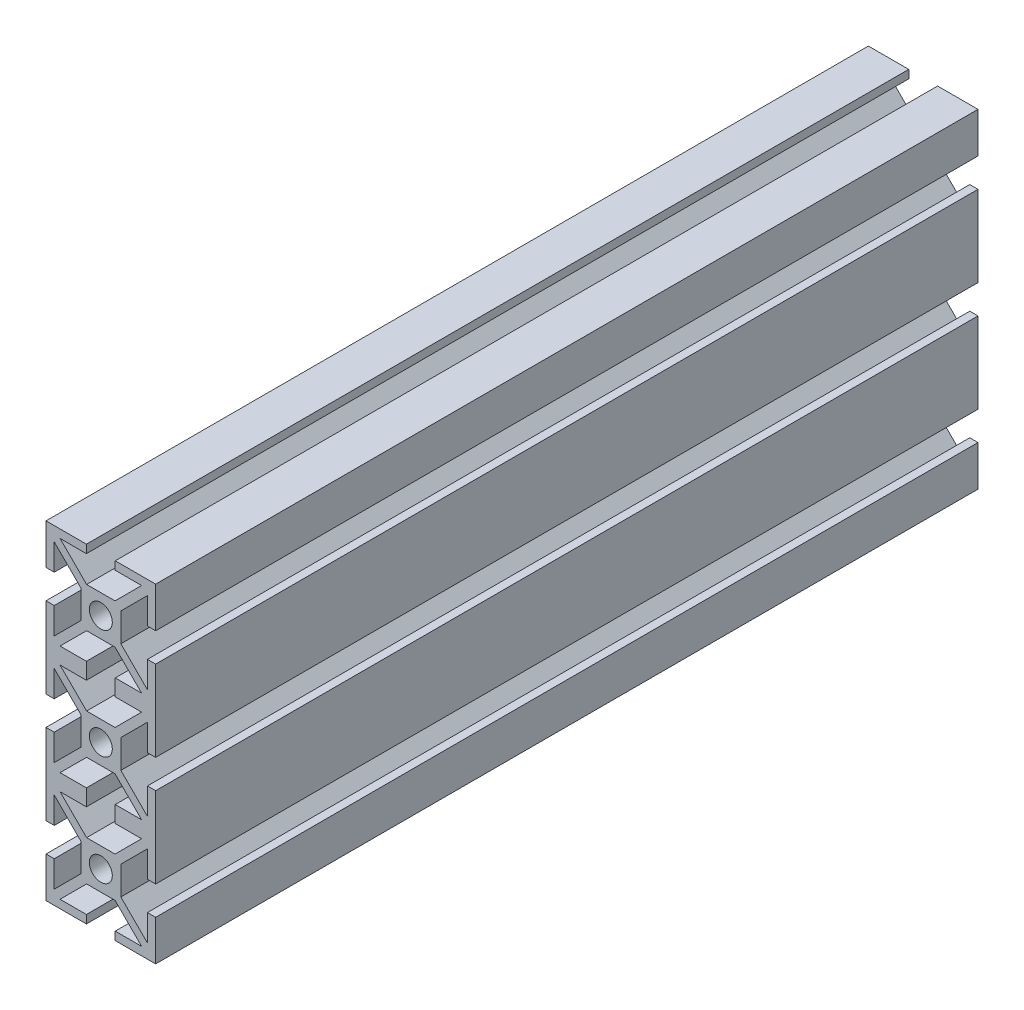
SolidWorks part; units mm, degrees
material "6061-T4 (SS)"
ref_plane "Front Plane" through (0, 0, 0) normal (0, 0, 1) x (1, 0, 0)
ref_plane "Top Plane" through (0, 0, 0) normal (0, 1, 0) x (1, 0, 0)
ref_plane "Right Plane" through (0, 0, 0) normal (1, 0, 0) x (0, 0, -1)
sketch "Sketch1" plane through (0, 0, 0) normal (0, 0, 1) x (1, 0, 0)
  line L0 (0, 20) -> (20, 0) construction
  line L1 (0, 0) -> (20, 0) construction
  line L2 (0, 0) -> (0, 20) construction
  line L3 (0, 20) -> (20, 20) construction
  line L4 (20, 0) -> (20, 20) construction
  line L5 (20, 20) -> (0, 0) construction
  line L6 (18.5, 1.5) -> (18.5, 0) construction
  line L7 (1.5, 1.5) -> (18.5, 1.5) construction
  line L8 (1.5, 1.5) -> (1.5, 18.5) construction
  line L9 (1.5, 18.5) -> (18.5, 18.5) construction
  line L10 (18.5, 1.5) -> (18.5, 18.5) construction
  line L11 (18.5, 1.5) -> (20, 1.5) construction
  line L12 (6.345, 12.5943) -> (1.5, 17.4393)
  line L13 (13.655, 6.345) -> (6.345, 6.345) construction
  line L14 (13.655, 6.345) -> (13.655, 13.655) construction
  line L15 (13.655, 13.655) -> (6.345, 13.655) construction
  line L16 (6.345, 6.345) -> (6.345, 13.655) construction
  line L17 (7.4057, 13.655) -> (2.5607, 18.5)
  line L18 (2.5607, 18.5) -> (2.0303, 17.9697) construction
  line L19 (2.0303, 17.9697) -> (1.5, 17.4393) construction
  line L20 (6.345, 7.4057) -> (6.345, 12.5943)
  line L21 (12.5943, 13.655) -> (17.4393, 18.5)
  line L22 (17.4393, 18.5) -> (17.9697, 17.9697) construction
  line L23 (17.9697, 17.9697) -> (18.5, 17.4393) construction
  line L24 (18.5, 17.4393) -> (13.655, 12.5943)
  line L25 (13.655, 7.4057) -> (18.5, 2.5607)
  line L26 (18.5, 2.5607) -> (17.9697, 2.0303) construction
  line L27 (17.4393, 1.5) -> (12.5943, 6.345)
  line L28 (7.4057, 6.345) -> (2.5607, 1.5)
  line L29 (17.9697, 2.0303) -> (17.4393, 1.5) construction
  line L30 (1.5, 2.5607) -> (6.345, 7.4057)
  line L31 (2.5607, 1.5) -> (2.0303, 2.0303) construction
  line L32 (2.0303, 2.0303) -> (1.5, 2.5607) construction
  line L33 (7.4057, 13.655) -> (12.5943, 13.655)
  line L34 (13.655, 12.5943) -> (13.655, 7.4057)
  line L36 (12.5943, 6.345) -> (7.4057, 6.345)
  line L37 (0, 10) -> (1.5, 10) construction
  line L38 (0.75, 12.63) -> (0.75, 10) construction
  line L39 (0.75, 10) -> (0.75, 7.37) construction
  line L40 (1.5, 12.63) -> (0, 12.63)
  line L41 (1.5, 7.37) -> (0, 7.37)
  line L42 (10, 1.5) -> (10, 0) construction
  line L43 (10, 0.75) -> (12.63, 0.75) construction
  line L44 (10, 0.75) -> (7.37, 0.75) construction
  line L45 (12.63, 0) -> (12.63, 1.5)
  line L46 (7.37, 1.5) -> (7.37, 0)
  line L47 (18.5, 12.63) -> (20, 12.63)
  line L48 (18.5, 7.37) -> (20, 7.37)
  line L49 (7.37, 20) -> (7.37, 18.5)
  line L50 (12.63, 20) -> (12.63, 18.5)
  line L51 (2.5607, 1.5) -> (7.37, 1.5)
  line L52 (12.63, 1.5) -> (17.4393, 1.5)
  line L53 (18.5, 7.37) -> (18.5, 2.5607)
  line L54 (18.5, 12.63) -> (18.5, 17.4393)
  line L55 (17.4393, 18.5) -> (12.63, 18.5)
  line L56 (7.37, 18.5) -> (2.5607, 18.5)
  line L57 (1.5, 17.4393) -> (1.5, 12.63)
  line L58 (1.5, 7.37) -> (1.5, 2.5607)
  line L59 (7.37, 0) -> (0, 0)
  line L60 (0, 0) -> (0, 7.37)
  line L61 (0, 12.63) -> (0, 20)
  line L62 (0, 20) -> (7.37, 20)
  line L63 (12.63, 20) -> (20, 20)
  line L64 (20, 20) -> (20, 12.63)
  line L65 (20, 7.37) -> (20, 0)
  line L66 (20, 0) -> (12.63, 0)
  circle A0 centre (10, 10) radius 2.095
  dimension "D2" = 4.19
  dimension "D6" = 5.26
  dimension "D1" = 20
  dimension "D3" = 1.5
  dimension "D4" = 3.655
  dimension "D5" = 1.5
extrude "Boss-Extrude1" add sketch "Sketch1" along normal blind 150
pattern_linear "LPattern1" count 3 spacing 20 along (0, -1, 0) of "Boss-Extrude1"
